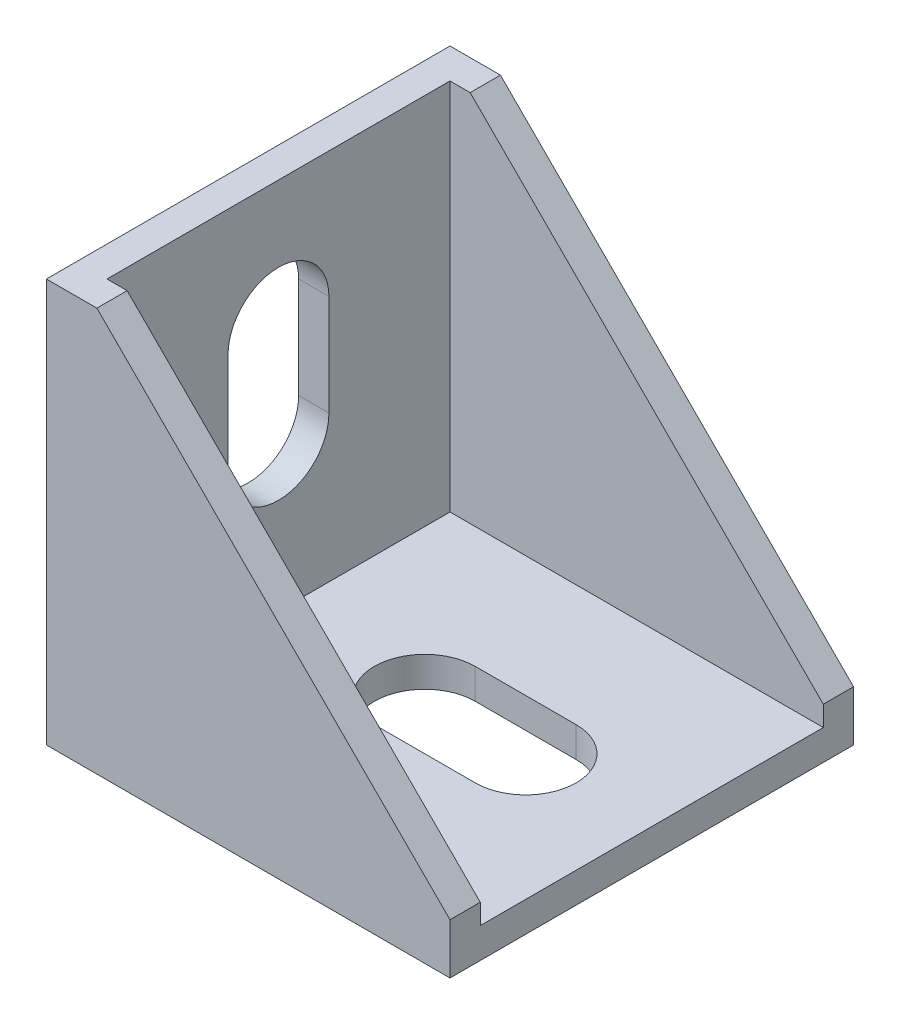
SolidWorks part; units mm, degrees
material "6063-T6"
ref_plane "Front Plane" through (0, 0, 0) normal (0, 0, 1) x (1, 0, 0)
ref_plane "Top Plane" through (0, 0, 0) normal (0, 1, 0) x (1, 0, 0)
ref_plane "Right Plane" through (0, 0, 0) normal (1, 0, 0) x (0, 0, -1)
sketch "Sketch1" plane through (0, 0, 0) normal (0, 0, 1) x (1, 0, 0)
  line L0 (40, 0) -> (0, 0)
  line L1 (0, 0) -> (0, 40)
  line L2 (0, 40) -> (5, 40)
  line L3 (5, 40) -> (40, 5)
  line L4 (40, 5) -> (40, 0)
  dimension "D1" = 40
  dimension "D2" = 5
extrude "Boss-Extrude1" add sketch "Sketch1" along normal mid plane 40
shell "Shell1" thickness 3
sketch "Sketch2" plane through (3, 0, 0) normal (1, 0, 0) x (0, 0, -1)
  line L1 (0, 27.5) -> (0, 17.5) construction
  line L2 (5, 27.5) -> (5, 17.5)
  line L3 (-5, 27.5) -> (-5, 17.5)
  line L4 (-17, 40) -> (17, 40) construction
  arc A0 (5, 27.5) -> (-5, 27.5) centre (0, 27.5) ccw
  arc A1 (-5, 17.5) -> (5, 17.5) centre (0, 17.5) ccw
  point P2 (0, 22.5)
  dimension "D3" = 7.5
  dimension "D1" = 10
  dimension "D2" = 10
extrude "Cut-Extrude1" cut sketch "Sketch2" against normal blind 40
ref_plane "Plane1" through (0, 0, 0) normal (0.7071, -0.7071, 0) x (0, 0, -1)
mirror "Mirror1" about plane through (0, 0, 0) normal (0.7071, -0.7071, 0) of "Cut-Extrude1"
